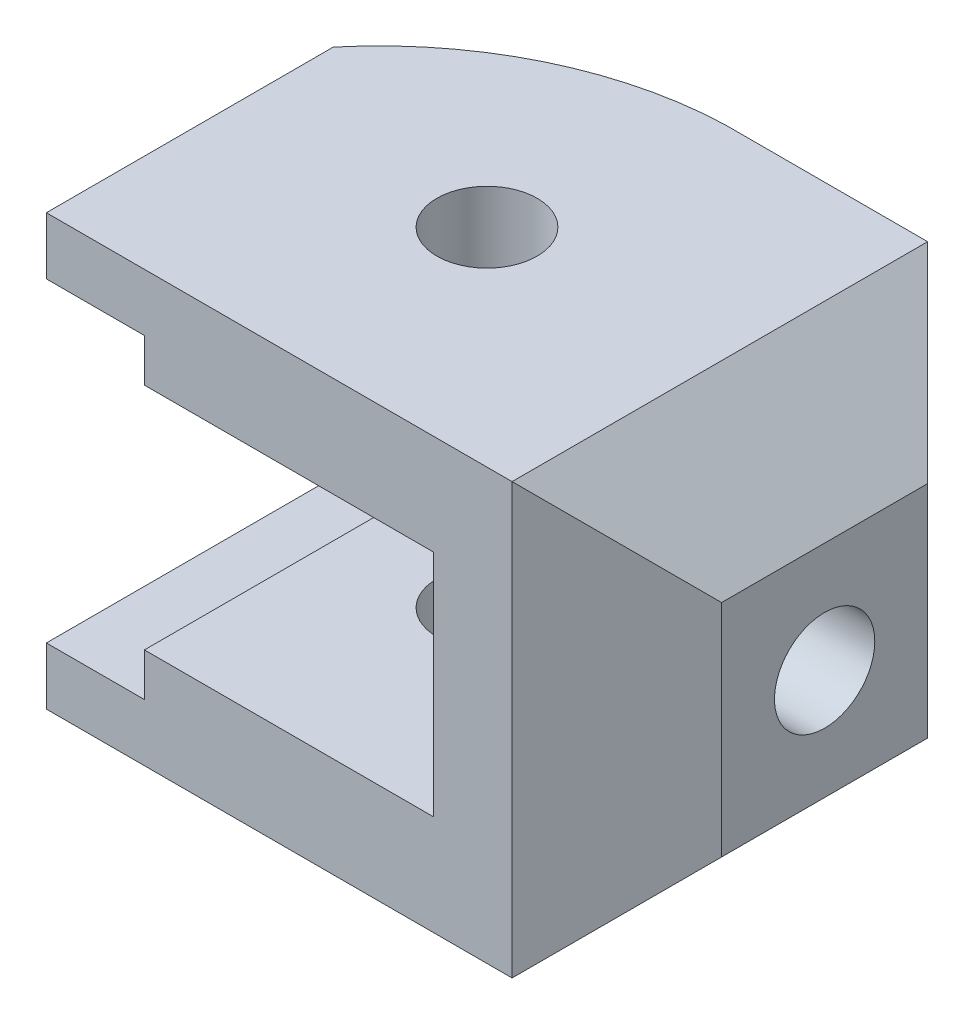
SolidWorks part; units mm, degrees
material "1060 Alloy"
ref_plane "Front Plane" through (0, 0, 0) normal (0, 0, 1) x (1, 0, 0)
ref_plane "Top Plane" through (0, 0, 0) normal (0, 1, 0) x (1, 0, 0)
ref_plane "Right Plane" through (0, 0, 0) normal (1, 0, 0) x (0, 0, -1)
sketch "Sketch1" plane through (0, 0, 0) normal (0, 0, 1) x (1, 0, 0)
  line L0 (0, 0) -> (65, 0)
  line L1 (65, 0) -> (79.6214, 14.6214)
  line L2 (79.6214, 14.6214) -> (79.6214, 45.3786)
  line L3 (79.6214, 45.3786) -> (65, 60)
  line L4 (65, 60) -> (0, 60)
  line L5 (0, 60) -> (0, 52)
  line L6 (0, 52) -> (13.686, 52)
  line L7 (13.686, 52) -> (13.686, 46)
  line L8 (13.686, 46) -> (54, 46)
  line L9 (54, 46) -> (54, 14)
  line L10 (54, 14) -> (13.686, 14)
  line L11 (13.686, 14) -> (13.686, 8)
  line L12 (13.686, 8) -> (0, 8)
  line L13 (0, 8) -> (0, 0)
  dimension "D1" = 60
  dimension "D2" = 45
  dimension "D3" = 45
  dimension "D4" = 11
  dimension "D5" = 11
  dimension "D6" = 8
  dimension "D7" = 8
  dimension "D8" = 6
  dimension "D9" = 6
  dimension "D10" = 65
extrude "Boss-Extrude1" add sketch "Sketch1" along normal blind 58
sketch "Sketch5" plane through (79.6214, 0, 0) normal (1, 0, 0) x (0, 0, -1)
  circle A0 centre (-29, 30) radius 7
  dimension "D1" = 14
extrude "Cut-Extrude1" cut sketch "Sketch5" against normal through all
sketch "Sketch7" plane through (0, 60, 0) normal (0, 1, 0) x (1, 0, 0)
  circle A0 centre (32.5, -29) radius 7
  dimension "D1" = 14
extrude "Cut-Extrude2" cut sketch "Sketch7" against normal through all
sketch "Sketch8" plane through (0, 0, 58) normal (0, 0, 1) x (1, 0, 0)
  line L0 (65, 60) -> (65, 0) construction
sketch "Sketch9" plane through (0, 0, 0) normal (0, 1, 0) x (1, 0, 0)
  line L0 (65, 0) -> (79.6214, 0)
  line L1 (79.6214, 0) -> (79.6214, -14.6214)
  line L2 (79.6214, -58) -> (79.6214, 0) construction
  line L3 (79.6214, -14.6214) -> (65, 0)
  line L4 (65, -58) -> (79.6214, -43.3786)
  line L5 (79.6214, -43.3786) -> (79.6214, -58)
  line L6 (79.6214, -58) -> (65, -58)
  dimension "D1" = 45
  dimension "D2" = 45
extrude "Cut-Extrude3" cut sketch "Sketch9" along normal through all
sketch "Sketch11" plane through (0, 60, 0) normal (0, 1, 0) x (1, 0, 0)
  line L0 (0, -58) -> (0, 0) construction
  line L1 (65, 0) -> (0, 0) construction
  line L2 (36.7164, 0) -> (0, 0)
  line L3 (0, 0) -> (0, -17.9549)
  arc A0 (0, -17.9549) -> (36.7164, 0) centre (38.4049, -49.9715) cw
  dimension "D1" = 50
extrude "Cut-Extrude4" cut sketch "Sketch11" against normal through all
equation "\"A\"= 58.00"
equation "\"B\"= 60.00"
equation "\"C\"= 65.00"
equation "\"D1@Sketch1\"=\"B\" "
equation "\"D1@Boss-Extrude1\"=\"A\""
